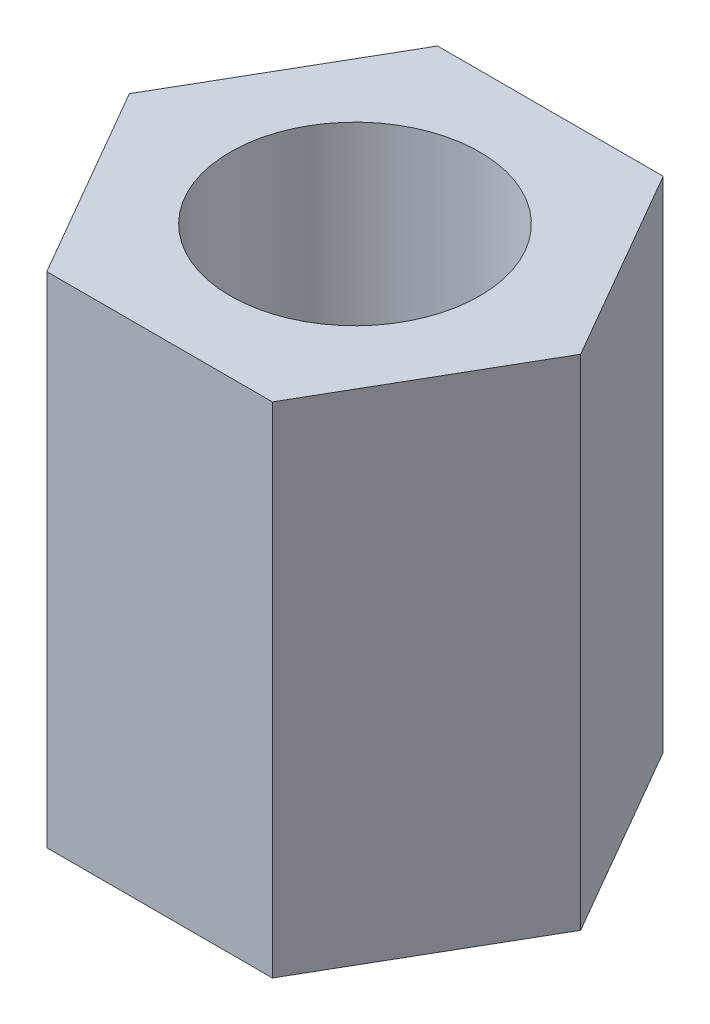
SolidWorks part; units mm, degrees
ref_plane "前视基准面" through (0, 0, 0) normal (0, 0, 1) x (1, 0, 0)
ref_plane "上视基准面" through (0, 0, 0) normal (0, 1, 0) x (1, 0, 0)
ref_plane "右视基准面" through (0, 0, 0) normal (1, 0, 0) x (0, 0, -1)
sketch "草图1" plane through (0, 0, 0) normal (0, 1, 0) x (1, 0, 0)
  line L1 (2.7135, 0) -> (1.3568, 2.35)
  line L2 (1.3568, 2.35) -> (-1.3568, 2.35)
  line L3 (-1.3568, 2.35) -> (-2.7135, 0)
  line L4 (-2.7135, 0) -> (-1.3568, -2.35)
  line L5 (-1.3568, -2.35) -> (1.3568, -2.35)
  line L6 (1.3568, -2.35) -> (2.7135, 0)
  circle A0 centre (0, 0) radius 2.35 construction
  circle A1 centre (0, 0) radius 1.5
extrude "凸台-拉伸1" add sketch "草图1" along normal blind 6
